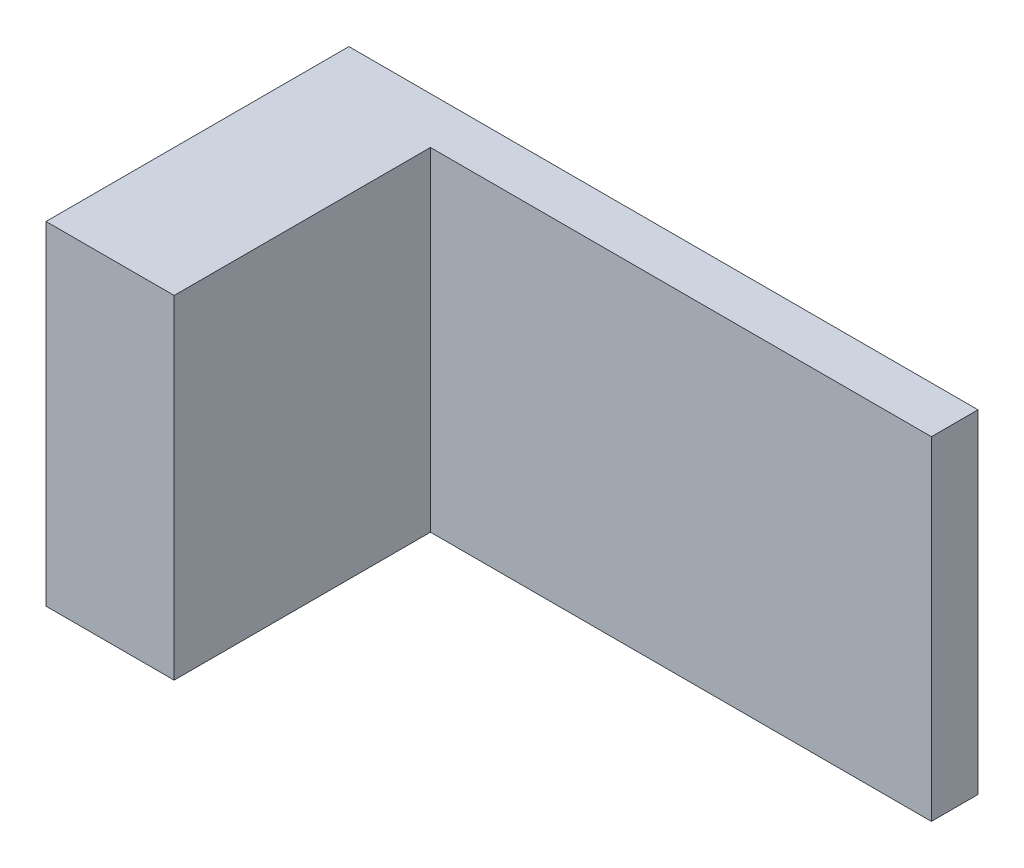
SolidWorks part; units mm, degrees
ref_plane "Front Plane" through (0, 0, 0) normal (0, 0, 1) x (1, 0, 0)
ref_plane "Top Plane" through (0, 0, 0) normal (0, 1, 0) x (1, 0, 0)
ref_plane "Right Plane" through (0, 0, 0) normal (1, 0, 0) x (0, 0, -1)
sketch "Sketch1" plane through (0, 0, 0) normal (0, 0, 1) x (1, 0, 0)
  line L1 (-13.5, 7.15) -> (13.5, 7.15)
  line L2 (-13.5, 7.15) -> (-13.5, -7.15)
  line L3 (-13.5, -7.15) -> (13.5, -7.15)
  line L4 (13.5, 7.15) -> (13.5, -7.15)
  line L5 (-13.5, 7.15) -> (13.5, -7.15) construction
  line L6 (-13.5, -7.15) -> (13.5, 7.15) construction
  point P0 (0, 0)
  dimension "D1" = 27
  dimension "D2" = 14.3
extrude "Boss-Extrude1" add sketch "Sketch1" along normal blind 2
sketch "Sketch2" plane through (0, 0, 2) normal (0, 0, 1) x (1, 0, 0)
  line L0 (-8, 7.15) -> (-8, -7.15)
  line L1 (13.5, 7.15) -> (-13.5, 7.15) construction
  line L2 (-13.5, -7.15) -> (13.5, -7.15) construction
  line L3 (-13.5, 7.15) -> (-13.5, -7.15) construction
  line L8 (13.5, -7.15) -> (13.5, 7.15)
  line L9 (13.5, 7.15) -> (-13.5, 7.15)
  line L10 (-13.5, 7.15) -> (-13.5, -7.15)
  line L11 (-13.5, -7.15) -> (13.5, -7.15)
  line L13 (-8, 7.15) -> (-13.5, 7.15)
  line L14 (-13.5, 7.15) -> (-13.5, -7.15)
  line L15 (-13.5, -7.15) -> (-8, -7.15)
  dimension "D1" = 5.5
  dimension "D2" = 0
extrude "Boss-Extrude2" add sketch "Sketch2" along normal blind 11
sketch "Sketch3" plane through (0, 0, 0) normal (0, 0, -1) x (-1, 0, 0)
  line L0 (-13.5, -7.15) -> (-13.5, 7.15) construction
  line L1 (-6.9, -2.35) -> (-9.4, -2.35)
  line L2 (-6.9, -2.35) -> (-6.9, 2.35)
  line L3 (-6.9, 2.35) -> (-9.4, 2.35)
  line L4 (-9.4, -2.35) -> (-9.4, 2.35)
  line L5 (-6.9, -2.35) -> (-9.4, 2.35) construction
  line L6 (-6.9, 2.35) -> (-9.4, -2.35) construction
  point P0 (-8.15, 0)
  dimension "D1" = 4.1
  dimension "D2" = 2.5
  dimension "D3" = 4.7
  dimension "D4" = 0
extrude "Boss-Extrude3" add sketch "Sketch3" along normal blind 1
sketch "Sketch4" plane through (0, 0, 0) normal (0, 0, -1) x (-1, 0, 0)
  line L4 (-13.5, 7.15) -> (-13.5, -7.15)
  line L5 (-13.5, -7.15) -> (13.5, -7.15)
  line L6 (13.5, -7.15) -> (13.5, 7.15)
  line L7 (13.5, 7.15) -> (-13.5, 7.15)
  line L8 (-13.5, 7.15) -> (-13.5, -7.15)
  line L9 (-13.5, -7.15) -> (13.5, -7.15)
  line L10 (13.5, -7.15) -> (13.5, 7.15)
  line L11 (13.5, 7.15) -> (-13.5, 7.15)
  dimension "D1" = 0
sketch "Sketch5" plane through (0, 0, -1) normal (0, 0, -1) x (-1, 0, 0)
  point P0 (-8.15, 0)
